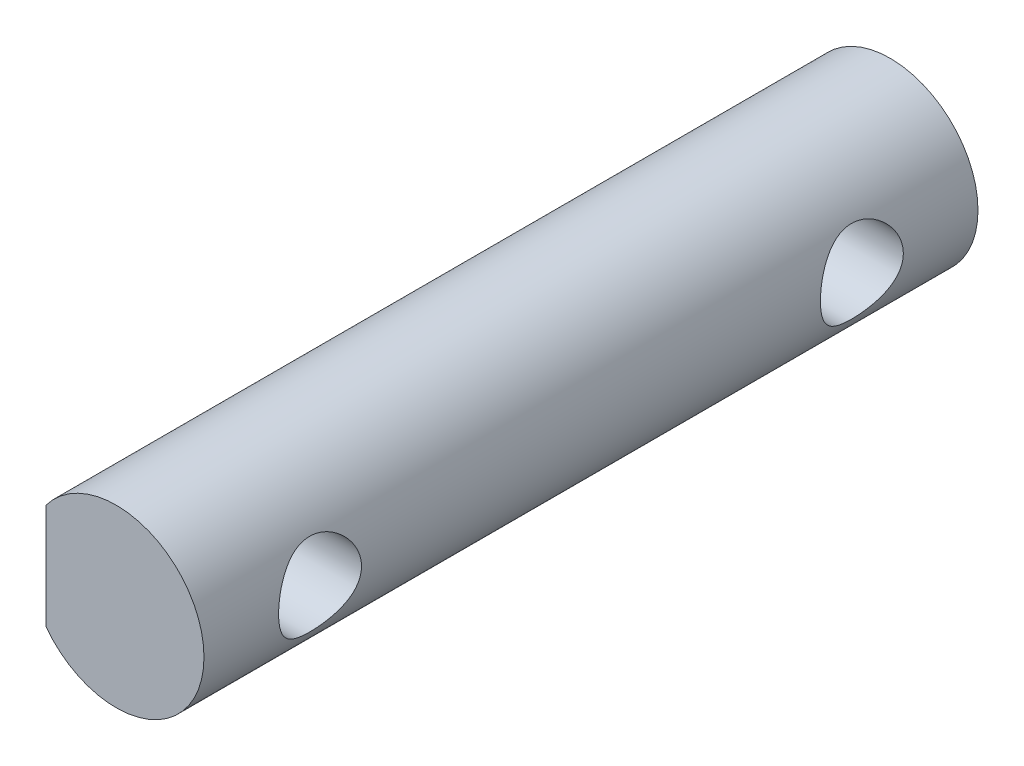
SolidWorks part; units mm, degrees
ref_plane "Front Plane" through (0, 0, 0) normal (0, 0, 1) x (1, 0, 0)
ref_plane "Top Plane" through (0, 0, 0) normal (0, 1, 0) x (1, 0, 0)
ref_plane "Right Plane" through (0, 0, 0) normal (1, 0, 0) x (0, 0, -1)
sketch "Sketch1" plane through (0, 0, 0) normal (0, 0, 1) x (1, 0, 0)
  line L0 (-2.54, 1.905) -> (-2.54, -1.905)
  arc A0 (-2.54, -1.905) -> (-2.54, 1.905) centre (0, 0) ccw
  point P5 (3.175, 0)
  dimension "D1" = 6.35
  dimension "D2" = 5.715
extrude "Boss-Extrude1" add sketch "Sketch1" along normal blind 28
sketch "Sketch3" plane through (-2.54, 0, 0) normal (-1, 0, 0) x (0, 0, 1)
  line L0 (4.2, 0) -> (23.8, 0) construction
  line L1 (28, -1.905) -> (0, -1.905) construction
  circle A0 centre (4.2, 0) radius 1.5
  circle A1 centre (23.8, 0) radius 1.5
  point P5 (14, -1.905)
  point P6 (14, 0)
  dimension "D2" = 3
  dimension "D1" = 19.6
extrude "Cut-Extrude1" cut sketch "Sketch3" against normal up to surface (5.715 mm away)
